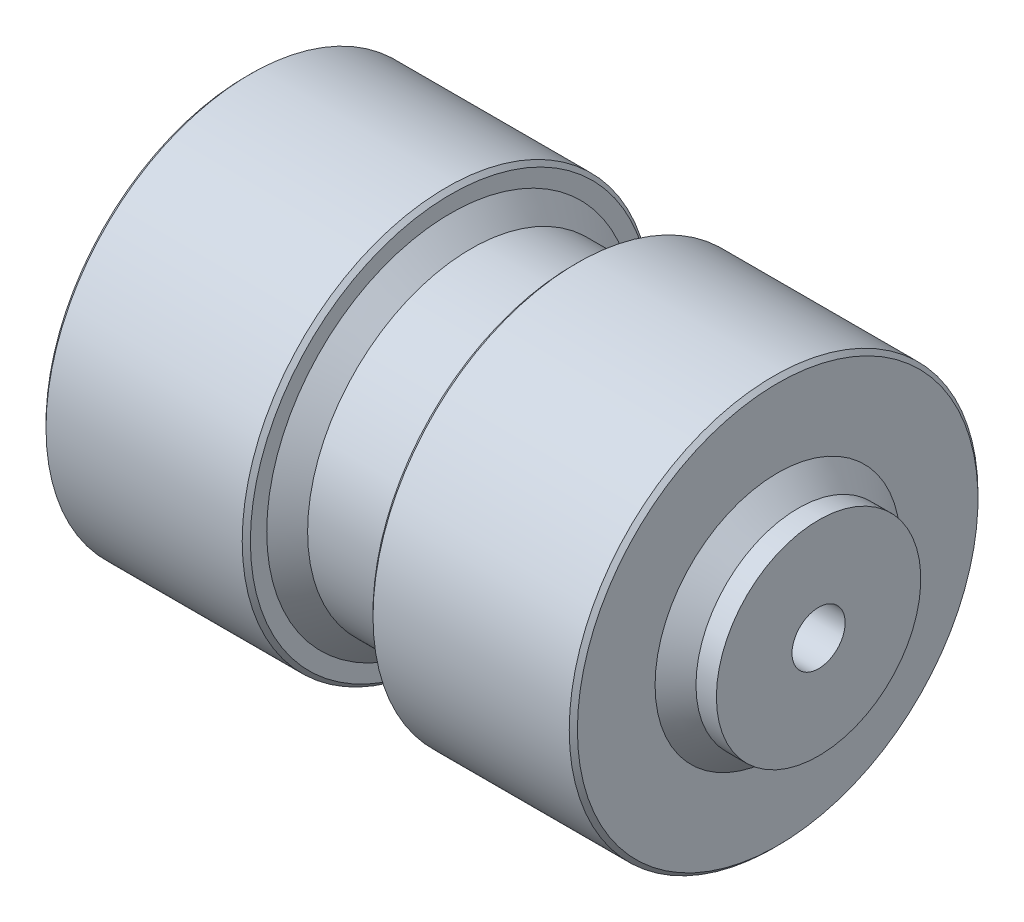
SolidWorks part; units mm, degrees
ref_plane "Ebene vorne" through (0, 0, 0) normal (0, 0, 1) x (1, 0, 0)
ref_plane "Ebene oben" through (0, 0, 0) normal (0, 1, 0) x (1, 0, 0)
ref_plane "Ebene rechts" through (0, 0, 0) normal (1, 0, 0) x (0, 0, -1)
sketch "Skizze1" plane through (0, 0, 0) normal (0, 0, 1) x (1, 0, 0)
  line L0 (-7.5, 0) -> (7.5, 0) construction
  line L1 (-7.5, 0) -> (-7.5, 2.5) construction
  line L2 (-7.5, 2.5) -> (-6.5, 2.5)
  line L3 (-6.5, 2.5) -> (-6.5, 5)
  line L4 (-6.5, 5) -> (-1.5, 5)
  line L5 (-1.5, 5) -> (-1.5, 4)
  line L6 (-1.5, 4) -> (1.5, 4)
  line L7 (1.5, 4) -> (1.5, 5)
  line L8 (1.5, 5) -> (6.5, 5)
  line L9 (6.5, 5) -> (6.5, 2.5)
  line L10 (6.5, 2.5) -> (7.5, 2.5)
  line L11 (7.5, 2.5) -> (7.5, 0) construction
  line L12 (7.5, 0) -> (-7.5, 0) construction
  line L13 (-7.5, 2.5) -> (-7.5, 0.65)
  line L14 (-7.5, 0.65) -> (7.5, 0.65)
  line L15 (7.5, 0.65) -> (7.5, 2.5)
  dimension "D1" = 15
  dimension "D2" = 2.5
  dimension "D3" = 5
  dimension "D4" = 1
  dimension "D5" = 1
  dimension "D6" = 5
  dimension "D7" = 1.3
revolve "Rotation1" add sketch "Skizze1" angle 360 about L0
chamfer "Fase1" distance 0.5 angle 45 4 edges at (1.5, 0, 4) (-1.5, 0, 4) (6.5, 0, 2.5) (-6.5, 0, 2.5)
chamfer "Fase2" distance 0.1 angle 45 4 edges at (6.5, 0, 5) (1.5, 0, 5) (-1.5, 0, 5) (-6.5, 0, 5)
